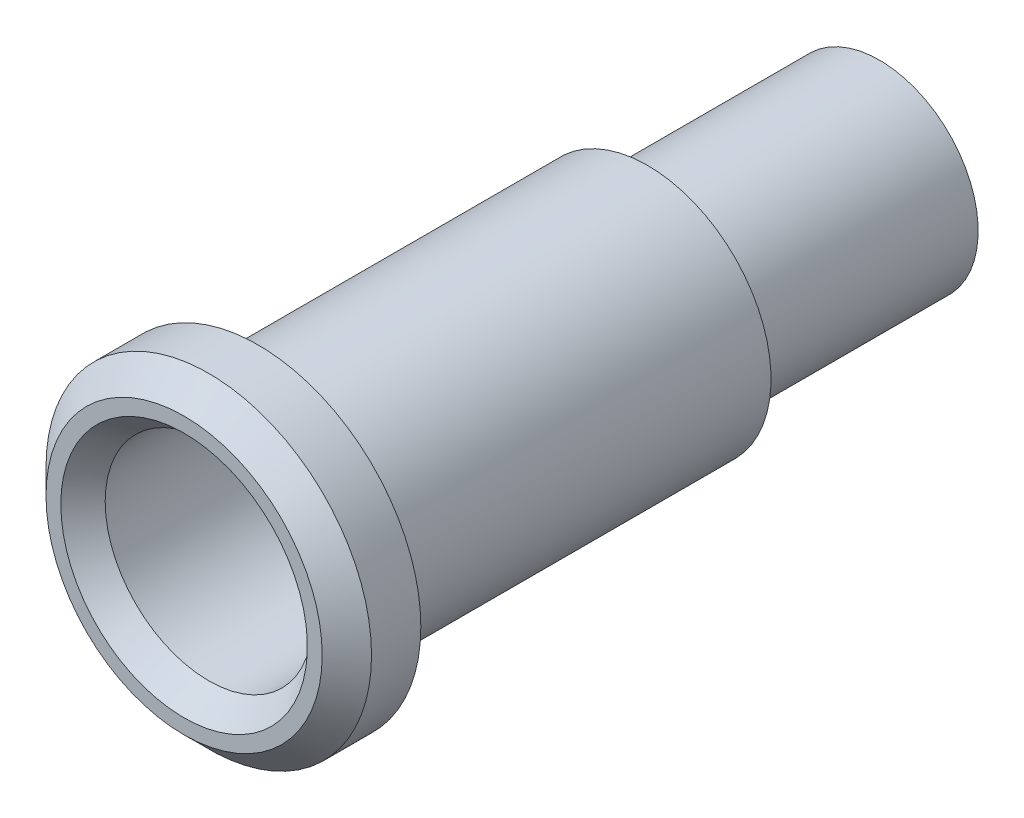
SolidWorks part; units mm, degrees
ref_plane "Front Plane" through (0, 0, 0) normal (0, 0, 1) x (1, 0, 0)
ref_plane "Top Plane" through (0, 0, 0) normal (0, 1, 0) x (1, 0, 0)
ref_plane "Right Plane" through (0, 0, 0) normal (1, 0, 0) x (0, 0, -1)
ref_plane "Plane1" through (0, 0, 0) normal (0, -1, 0) x (1, 0, 0)
sketch "Sketch1" plane through (0, 0, 0) normal (0, -1, 0) x (1, 0, 0)
  line L0 (2.1, -6.9) -> (1.425, -6.9)
  line L1 (1.425, -6.9) -> (1.425, -7.9)
  line L2 (1.425, -7.9) -> (1, -7.9)
  line L3 (1, -7.9) -> (1, -12.6)
  line L4 (1, -12.6) -> (2, -12.6)
  line L5 (2, -12.6) -> (2, -7.9)
  line L6 (2, -7.9) -> (2.5, -7.9)
  line L7 (2.5, -7.9) -> (2.5, 0)
  line L8 (2.5, 0) -> (3.3, 0)
  line L9 (3.3, 0) -> (3.3, 1)
  line L10 (3.3, 1) -> (2.8, 1.5)
  line L11 (2.8, 1.5) -> (2.5, 1.5)
  line L12 (2.5, 1.5) -> (2.1, 1)
  line L13 (2.1, 1) -> (2.1, -6.9)
  line L14 (0, 1.5) -> (0, -12.6) construction
revolve "Revolve1" add sketch "Sketch1" angle 360 about L14
